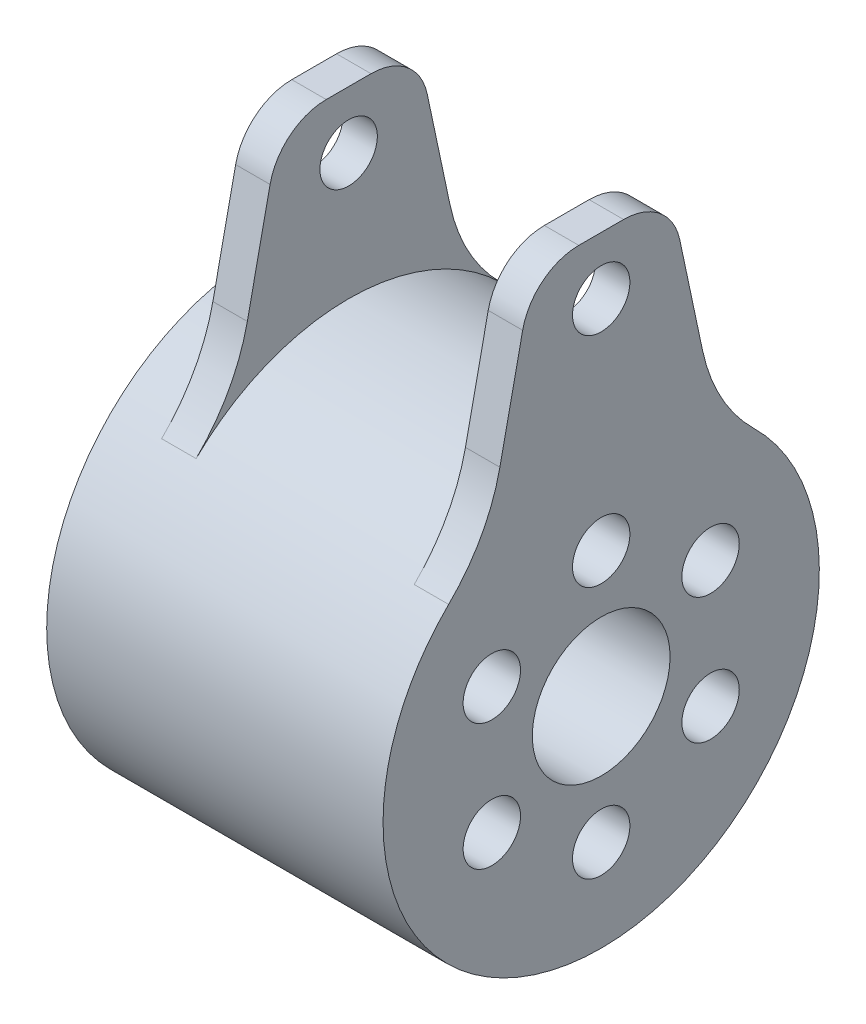
SolidWorks part; units mm, degrees
material "1023 碳钢板 (SS)"
ref_plane "前视基准面" through (0, 0, 0) normal (0, 0, 1) x (1, 0, 0)
ref_plane "上视基准面" through (0, 0, 0) normal (0, 1, 0) x (1, 0, 0)
ref_plane "右视基准面" through (0, 0, 0) normal (1, 0, 0) x (0, 0, -1)
sketch "草图1" plane through (0, 0, 0) normal (1, 0, 0) x (0, 0, -1)
  circle A0 centre (0, 0) radius 19
  circle A1 centre (0, -15) radius 2
  circle A2 centre (0, 13.5) radius 2
  circle A3 centre (11.6913, -6.75) radius 2
  circle A4 centre (-12.9904, 7.5) radius 2
  circle A5 centre (-11.6913, -6.75) radius 2
  circle A6 centre (12.9904, 7.5) radius 2
  circle A7 centre (0, 0) radius 11
  point P17 (0, 0)
  dimension "D1" = 38
  dimension "D2" = 4
  dimension "D3" = 4
  dimension "D4" = 13.5
  dimension "D5" = 15
  dimension "D7" = 22
  dimension "D6" = 3
extrude "凸台-拉伸1" add sketch "草图1" along normal blind 3
sketch "草图3" plane through (3, 0, 0) normal (1, 0, 0) x (0, 0, -1)
  arc A0 (-2.7954, 10.6389) -> (2.7954, 10.6389) centre (0, 13.5) ccw
  circle A1 centre (0, 0) radius 11 construction
  arc A2 (2.7954, 10.6389) -> (-2.7954, 10.6389) centre (0, 0) ccw
  arc A3 (10.6112, -2.8986) -> (7.8159, -7.7403) centre (11.6913, -6.75) ccw
  arc A4 (7.8159, -7.7403) -> (10.6112, -2.8986) centre (0, 0) ccw
  arc A5 (-7.8159, -7.7403) -> (-10.6112, -2.8986) centre (-11.6913, -6.75) ccw
  arc A6 (-10.6112, -2.8986) -> (-7.8159, -7.7403) centre (0, 0) ccw
  circle A7 centre (0, 13.5) radius 2 construction
  point P14 (0, 0)
  dimension "D1" = 8
  dimension "D2" = 3
extrude "凸台-拉伸2" add sketch "草图3" against normal up to surface (3 mm away) up to face at (0, 0, -19)
fillet "圆角1" radius 3 6 edges at (1.5, 10.6389, -2.7954) (1.5, 10.6389, 2.7954) (1.5, -7.7403, -7.8159) (1.5, -2.8986, -10.6112) (1.5, -2.8986, 10.6112) (1.5, -7.7403, 7.8159)
sketch "草图5" plane through (3, 0, 0) normal (1, 0, 0) x (0, 0, -1)
  line L0 (0, 0) -> (0, 54.073) construction
  line L1 (-6, 35) -> (-10, 16.1555)
  line L2 (6, 35) -> (10, 16.1555)
  line L3 (-6, 35) -> (6, 35)
  circle A0 centre (0, 30) radius 2.5
  circle A2 centre (0, 0) radius 19 construction
  arc A3 (10, 16.1555) -> (-10, 16.1555) centre (0, 0) ccw
  dimension "D1" = 30
  dimension "D2" = 5
  dimension "D3" = 5
  dimension "D4" = 20
  dimension "D5" = 12
extrude "凸台-拉伸3" add sketch "草图5" against normal up to surface (3 mm away) up to face at (0, 0, -19)
fillet "圆角2" radius 16 2 edges at (1.5, 16.1555, -10) (1.5, 16.1555, 10)
fillet "圆角3" radius 5 2 edges at (1.5, 35, -6) (1.5, 35, 6)
chamfer "倒角1" [suppressed] distance 2 angle 45
sketch "草图6" [suppressed] plane through (0, 0, 0) normal (-1, 0, 0) x (0, 0, 1)
  circle A0 centre (0, -15) radius 4
  circle A1 centre (0, -15) radius 5
  circle A2 centre (-12.9904, 7.5) radius 4
  circle A3 centre (-12.9904, 7.5) radius 5
  circle A4 centre (12.9904, 7.5) radius 4
  circle A5 centre (12.9904, 7.5) radius 5
  point P13 (0, 0)
  dimension "D1" = 8
  dimension "D2" = 10
  dimension "D3" = 3
extrude "凸台-拉伸4" [suppressed] add sketch "草图6" against normal up to surface (3 mm away)
sketch "草图7" [suppressed] plane through (0, 0, 0) normal (-1, 0, 0) x (0, 0, 1)
  circle A0 centre (0, -15) radius 4
  dimension "D1" = 8
sketch "草图8" plane through (0, 0, 0) normal (-1, 0, 0) x (0, 0, 1)
  arc A0 (9.5574, -3.3668) -> (10.9407, -1.1404) centre (7.9569, -0.8294) ccw construction
  arc A1 (9.5574, -3.3668) -> (7.6944, -6.5935) centre (11.6913, -6.75) ccw construction
  arc A2 (6.458, -8.9048) -> (7.6944, -6.5935) centre (4.6967, -6.4762) ccw construction
  arc A3 (-6.458, -8.9048) -> (6.458, -8.9048) centre (0, 0) ccw construction
  arc A4 (-7.6944, -6.5935) -> (-6.458, -8.9048) centre (-4.6967, -6.4762) ccw construction
  arc A5 (-7.6944, -6.5935) -> (-9.5574, -3.3668) centre (-11.6913, -6.75) ccw construction
  arc A6 (-10.9407, -1.1404) -> (-9.5574, -3.3668) centre (-7.9569, -0.8294) ccw construction
  arc A7 (10.9407, -1.1404) -> (4.4828, 10.0451) centre (0, 0) ccw construction
  arc A8 (4.4828, 10.0451) -> (1.863, 9.9603) centre (3.2602, 7.3056) ccw construction
  arc A9 (-1.863, 9.9603) -> (1.863, 9.9603) centre (0, 13.5) ccw construction
  arc A10 (-1.863, 9.9603) -> (-4.4828, 10.0451) centre (-3.2602, 7.3056) ccw construction
  arc A11 (-4.4828, 10.0451) -> (-10.9407, -1.1404) centre (0, 0) ccw construction
  arc A12 (9.5574, -3.3668) -> (10.9407, -1.1404) centre (7.9569, -0.8294) ccw
  arc A13 (9.5574, -3.3668) -> (7.6944, -6.5935) centre (11.6913, -6.75) ccw
  arc A14 (6.458, -8.9048) -> (7.6944, -6.5935) centre (4.6967, -6.4762) ccw
  arc A15 (-6.458, -8.9048) -> (6.458, -8.9048) centre (0, 0) ccw
  arc A16 (-7.6944, -6.5935) -> (-6.458, -8.9048) centre (-4.6967, -6.4762) ccw
  arc A17 (-7.6944, -6.5935) -> (-9.5574, -3.3668) centre (-11.6913, -6.75) ccw
  arc A18 (-10.9407, -1.1404) -> (-9.5574, -3.3668) centre (-7.9569, -0.8294) ccw
  arc A19 (10.9407, -1.1404) -> (4.4828, 10.0451) centre (0, 0) ccw
  arc A20 (4.4828, 10.0451) -> (1.863, 9.9603) centre (3.2602, 7.3056) ccw
  arc A21 (-1.863, 9.9603) -> (1.863, 9.9603) centre (0, 13.5) ccw
  arc A22 (-1.863, 9.9603) -> (-4.4828, 10.0451) centre (-3.2602, 7.3056) ccw
  arc A23 (-4.4828, 10.0451) -> (-10.9407, -1.1404) centre (0, 0) ccw
  circle A24 centre (0, 0) radius 19
  circle A25 centre (0, -15) radius 2 construction
  circle A26 centre (-11.6913, -6.75) radius 2 construction
  circle A27 centre (11.6913, -6.75) radius 2 construction
  circle A28 centre (12.9904, 7.5) radius 2 construction
  circle A29 centre (0, 13.5) radius 2 construction
  circle A30 centre (-12.9904, 7.5) radius 2 construction
  circle A31 centre (0, -15) radius 2
  circle A32 centre (-11.6913, -6.75) radius 2
  circle A33 centre (11.6913, -6.75) radius 2
  circle A34 centre (12.9904, 7.5) radius 2
  circle A35 centre (0, 13.5) radius 2
  circle A36 centre (-12.9904, 7.5) radius 2
extrude "凸台-拉伸5" add sketch "草图8" along normal blind 8
sketch "草图9" plane through (3, 0, 0) normal (1, 0, 0) x (0, 0, -1)
  line L3 (8.8237, 21.6973) -> (6.8409, 31.0382)
  line L4 (1.9499, 35) -> (-1.9499, 35)
  line L5 (-6.8409, 31.0382) -> (-8.8237, 21.6973)
  line L6 (8.8237, 21.6973) -> (6.8409, 31.0382)
  line L7 (1.9499, 35) -> (-1.9499, 35)
  line L8 (-6.8409, 31.0382) -> (-8.8237, 21.6973)
  circle A0 centre (0, -15) radius 2 construction
  circle A1 centre (11.6913, -6.75) radius 2 construction
  circle A2 centre (-11.6913, -6.75) radius 2 construction
  arc A3 (6.458, -8.9048) -> (7.6944, -6.5935) centre (4.6967, -6.4762) ccw construction
  arc A4 (-6.458, -8.9048) -> (6.458, -8.9048) centre (0, 0) ccw construction
  arc A5 (6.8409, 31.0382) -> (1.9499, 35) centre (1.9499, 30) ccw
  arc A6 (-1.9499, 35) -> (-6.8409, 31.0382) centre (-1.9499, 30) ccw
  arc A7 (-13.2864, 13.582) -> (-8.8237, 21.6973) centre (-24.475, 25.0195) ccw
  arc A8 (-13.2864, 13.582) -> (13.2864, 13.582) centre (0, 0) ccw
  arc A9 (8.8237, 21.6973) -> (13.2864, 13.582) centre (24.475, 25.0195) ccw
  arc A10 (6.8409, 31.0382) -> (1.9499, 35) centre (1.9499, 30) ccw
  arc A11 (-1.9499, 35) -> (-6.8409, 31.0382) centre (-1.9499, 30) ccw
  arc A12 (-13.2864, 13.582) -> (-8.8237, 21.6973) centre (-24.475, 25.0195) ccw
  arc A13 (-13.2864, 13.582) -> (13.2864, 13.582) centre (0, 0) ccw
  arc A14 (8.8237, 21.6973) -> (13.2864, 13.582) centre (24.475, 25.0195) ccw
  arc A15 (-7.6944, -6.5935) -> (-6.458, -8.9048) centre (-4.6967, -6.4762) ccw construction
  arc A16 (9.5574, -3.3668) -> (7.6944, -6.5935) centre (11.6913, -6.75) ccw construction
  arc A17 (9.5574, -3.3668) -> (10.9407, -1.1404) centre (7.9569, -0.8294) ccw construction
  arc A18 (-7.6944, -6.5935) -> (-9.5574, -3.3668) centre (-11.6913, -6.75) ccw construction
  arc A19 (-10.9407, -1.1404) -> (-9.5574, -3.3668) centre (-7.9569, -0.8294) ccw construction
  arc A20 (10.9407, -1.1404) -> (4.4828, 10.0451) centre (0, 0) ccw construction
  arc A21 (-4.4828, 10.0451) -> (-10.9407, -1.1404) centre (0, 0) ccw construction
  arc A22 (4.4828, 10.0451) -> (1.863, 9.9603) centre (3.2602, 7.3056) ccw construction
  arc A23 (-1.863, 9.9603) -> (1.863, 9.9603) centre (0, 13.5) ccw construction
  arc A24 (-1.863, 9.9603) -> (-4.4828, 10.0451) centre (-3.2602, 7.3056) ccw construction
  circle A25 centre (12.9904, 7.5) radius 2 construction
  circle A26 centre (-12.9904, 7.5) radius 2 construction
  circle A27 centre (0, 13.5) radius 2 construction
  circle A28 centre (0, 30) radius 2.5 construction
  circle A29 centre (0, -15) radius 2
  circle A30 centre (11.6913, -6.75) radius 2
  circle A31 centre (-11.6913, -6.75) radius 2
  arc A32 (6.458, -8.9048) -> (7.6944, -6.5935) centre (4.6967, -6.4762) ccw
  arc A33 (-6.458, -8.9048) -> (6.458, -8.9048) centre (0, 0) ccw
  arc A34 (-7.6944, -6.5935) -> (-6.458, -8.9048) centre (-4.6967, -6.4762) ccw
  arc A35 (9.5574, -3.3668) -> (7.6944, -6.5935) centre (11.6913, -6.75) ccw
  arc A36 (9.5574, -3.3668) -> (10.9407, -1.1404) centre (7.9569, -0.8294) ccw
  arc A37 (-7.6944, -6.5935) -> (-9.5574, -3.3668) centre (-11.6913, -6.75) ccw
  arc A38 (-10.9407, -1.1404) -> (-9.5574, -3.3668) centre (-7.9569, -0.8294) ccw
  arc A39 (10.9407, -1.1404) -> (4.4828, 10.0451) centre (0, 0) ccw
  arc A40 (-4.4828, 10.0451) -> (-10.9407, -1.1404) centre (0, 0) ccw
  arc A41 (4.4828, 10.0451) -> (1.863, 9.9603) centre (3.2602, 7.3056) ccw
  arc A42 (-1.863, 9.9603) -> (1.863, 9.9603) centre (0, 13.5) ccw
  arc A43 (-1.863, 9.9603) -> (-4.4828, 10.0451) centre (-3.2602, 7.3056) ccw
  circle A44 centre (12.9904, 7.5) radius 2
  circle A45 centre (-12.9904, 7.5) radius 2
  circle A46 centre (0, 13.5) radius 2
  circle A47 centre (0, 30) radius 2.5
  dimension "D1" = 0
extrude "凸台-拉伸6" add sketch "草图9" along normal blind 25
ref_plane "基准面1" through (6, 0, 0) normal (-1, 0, 0) x (0, 0, 1)
sketch "草图11" plane through (6, 0, 0) normal (-1, 0, 0) x (0, 0, 1)
  line L3 (-6.8409, 31.0382) -> (-8.8237, 21.6973)
  line L4 (1.9499, 35) -> (-1.9499, 35)
  line L5 (8.8237, 21.6973) -> (6.8409, 31.0382)
  line L6 (-6.8409, 31.0382) -> (-8.8237, 21.6973)
  line L7 (1.9499, 35) -> (-1.9499, 35)
  line L8 (8.8237, 21.6973) -> (6.8409, 31.0382)
  arc A0 (13.2864, 13.582) -> (-13.2864, 13.582) centre (0, 0) ccw
  arc A5 (-13.2864, 13.582) -> (-8.8237, 21.6973) centre (-24.475, 25.0195) ccw
  arc A6 (-1.9499, 35) -> (-6.8409, 31.0382) centre (-1.9499, 30) ccw
  arc A7 (6.8409, 31.0382) -> (1.9499, 35) centre (1.9499, 30) ccw
  arc A8 (8.8237, 21.6973) -> (13.2864, 13.582) centre (24.475, 25.0195) ccw
  arc A9 (-13.2864, 13.582) -> (13.2864, 13.582) centre (0, 0) ccw
  arc A10 (-13.2864, 13.582) -> (-8.8237, 21.6973) centre (-24.475, 25.0195) ccw
  arc A11 (-1.9499, 35) -> (-6.8409, 31.0382) centre (-1.9499, 30) ccw
  arc A12 (6.8409, 31.0382) -> (1.9499, 35) centre (1.9499, 30) ccw
  arc A13 (8.8237, 21.6973) -> (13.2864, 13.582) centre (24.475, 25.0195) ccw
  dimension "D1" = 0
extrude "切除-拉伸1" cut sketch "草图11" against normal blind 19
sketch "草图12" plane through (28, 0, 0) normal (1, 0, 0) x (0, 0, -1)
  circle A0 centre (0, 0) radius 11
  circle A1 centre (0, 0) radius 19
extrude "凸台-拉伸7" add sketch "草图12" against normal blind 36
sketch "草图13" plane through (28, 0, 0) normal (1, 0, 0) x (0, 0, -1)
  line L0 (0, 30) -> (0, -27.4941) construction
  arc A0 (-10.5222, 3.2069) -> (-10.5222, -3.2069) centre (0, 0) ccw
  arc A2 (-2.4838, 10.7159) -> (2.4838, 10.7159) centre (0, 11) ccw
  arc A3 (8.0383, 7.509) -> (10.5222, 3.2069) centre (9.5263, 5.5) ccw
  arc A4 (10.5222, -3.2069) -> (8.0383, -7.509) centre (9.5263, -5.5) ccw
  arc A5 (2.4838, -10.7159) -> (-2.4838, -10.7159) centre (0, -11) ccw
  arc A6 (-8.0383, -7.509) -> (-10.5222, -3.2069) centre (-9.5263, -5.5) ccw
  arc A7 (-10.5222, 3.2069) -> (-8.0383, 7.509) centre (-9.5263, 5.5) ccw
  circle A8 centre (0, 0) radius 6
  arc A9 (-2.4838, 10.7159) -> (-8.0383, 7.509) centre (0, 0) ccw
  arc A10 (8.0383, 7.509) -> (2.4838, 10.7159) centre (0, 0) ccw
  arc A11 (10.5222, -3.2069) -> (10.5222, 3.2069) centre (0, 0) ccw
  arc A12 (2.4838, -10.7159) -> (8.0383, -7.509) centre (0, 0) ccw
  arc A13 (-8.0383, -7.509) -> (-2.4838, -10.7159) centre (0, 0) ccw
  point P21 (0, 0)
  dimension "D1" = 6
extrude "凸台-拉伸8" add sketch "草图13" against normal blind 36
sketch "草图14" plane through (28, 0, 0) normal (1, 0, 0) x (0, 0, -1)
  circle A0 centre (0, 11) radius 2.5
  circle A1 centre (-9.5263, 5.5) radius 2.5
  arc A2 (-8.0383, 7.509) -> (-10.5222, 3.2069) centre (0, 0) ccw construction
  circle A3 centre (-9.5263, -5.5) radius 2.5
  circle A4 centre (0, -11) radius 2.5
  circle A5 centre (9.5263, -5.5) radius 2.5
  circle A6 centre (9.5263, 5.5) radius 2.5
extrude "切除-拉伸2" cut sketch "草图14" against normal blind 36
sketch "草图15" plane through (-8, 0, 0) normal (-1, 0, 0) x (0, 0, 1)
  circle A0 centre (0, 0) radius 28.7129
extrude "切除-拉伸3" cut sketch "草图15" against normal blind 6.7
sketch "草图17" plane through (-1.3, 0, 0) normal (-1, 0, 0) x (0, 0, 1)
  circle A0 centre (-5.5, -9.5263) radius 2
  circle A1 centre (-5.5, 9.5263) radius 1.5
  circle A2 centre (5.5, 9.5263) radius 2
  circle A3 centre (5.5, -9.5263) radius 1.5
extrude "凸台-拉伸9" add sketch "草图17" along normal blind 3.8
chamfer "倒角2" distance 0.5 angle 45 4 edges at (-5.1, -9.5263, -3.5) (-5.1, -9.5263, 7) (-5.1, 9.5263, -4) (-5.1, 9.5263, 7.5)
sketch "草图18" plane through (28, 0, 0) normal (1, 0, 0) x (0, 0, -1)
sketch "草图19" plane through (0, 0, 0) normal (-1, 0, 0) x (0, 0, 1)
  line L3 (8.8237, 21.6973) -> (6.8409, 31.0382)
  line L4 (1.9499, 35) -> (-1.9499, 35)
  line L5 (-6.8409, 31.0382) -> (-8.8237, 21.6973)
  line L6 (8.8237, 21.6973) -> (6.8409, 31.0382)
  line L7 (1.9499, 35) -> (-1.9499, 35)
  line L8 (-6.8409, 31.0382) -> (-8.8237, 21.6973)
  arc A5 (13.2864, 13.582) -> (-13.2864, 13.582) centre (0, 0) ccw
  arc A6 (8.8237, 21.6973) -> (13.2864, 13.582) centre (24.475, 25.0195) ccw
  arc A7 (6.8409, 31.0382) -> (1.9499, 35) centre (1.9499, 30) ccw
  arc A8 (-1.9499, 35) -> (-6.8409, 31.0382) centre (-1.9499, 30) ccw
  arc A9 (-13.2864, 13.582) -> (-8.8237, 21.6973) centre (-24.475, 25.0195) ccw
  arc A10 (13.2864, 13.582) -> (-13.2864, 13.582) centre (0, 0) ccw
  arc A11 (8.8237, 21.6973) -> (13.2864, 13.582) centre (24.475, 25.0195) ccw
  arc A12 (6.8409, 31.0382) -> (1.9499, 35) centre (1.9499, 30) ccw
  arc A13 (-1.9499, 35) -> (-6.8409, 31.0382) centre (-1.9499, 30) ccw
  arc A14 (-13.2864, 13.582) -> (-8.8237, 21.6973) centre (-24.475, 25.0195) ccw
  dimension "D1" = 0
extrude "切除-拉伸4" cut sketch "草图19" against normal blind 3
move or copy body "实体-移动/复制6" [suppressed] bodies to move or copy 113
move or copy body "实体-移动/复制7" [suppressed] bodies to move or copy 118
move or copy body "实体-移动/复制5" [suppressed] bodies to move or copy 113
move or copy body "实体-移动/复制4" [suppressed] bodies to move or copy 118
move or copy body "实体-移动/复制3" [suppressed] bodies to move or copy 113
move or copy body "实体-移动/复制2" [suppressed] bodies to move or copy 113
move or copy body "实体-移动/复制1" [suppressed] bodies to move or copy 109
